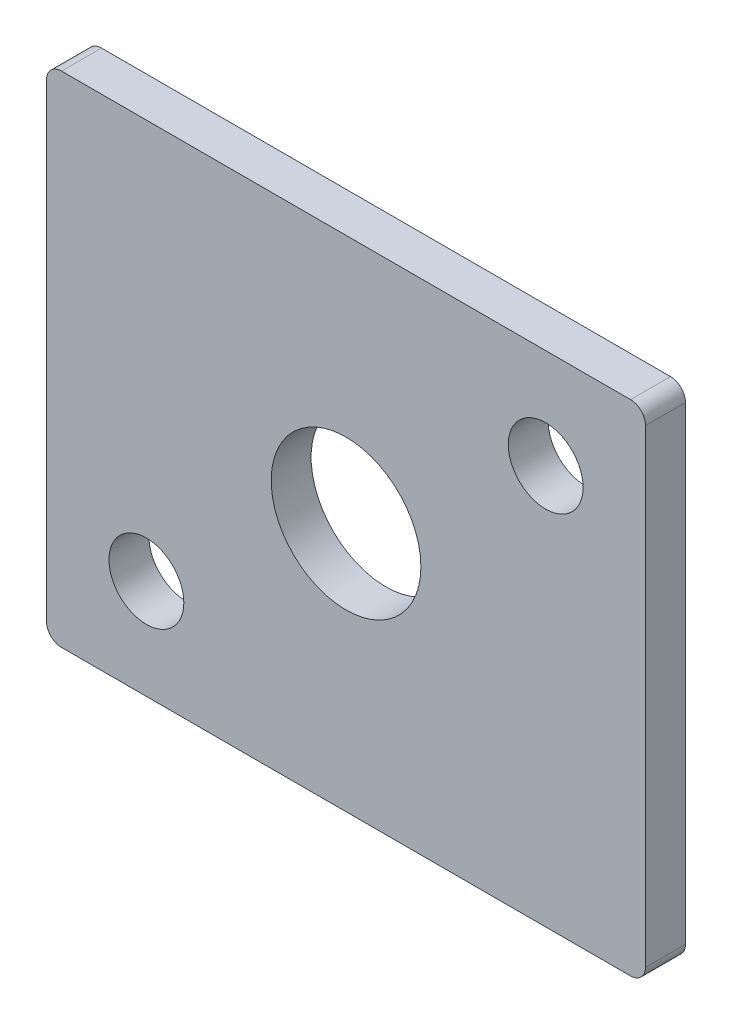
SolidWorks part; units mm, degrees
material "Messing"
ref_plane "Ebene vorne" through (0, 0, 0) normal (0, 0, 1) x (1, 0, 0)
ref_plane "Ebene oben" through (0, 0, 0) normal (0, 1, 0) x (1, 0, 0)
ref_plane "Ebene rechts" through (0, 0, 0) normal (1, 0, 0) x (0, 0, -1)
sketch "Skizze1" plane through (0, 0, 0) normal (0, 0, 1) x (1, 0, 0)
  line L1 (0, 0) -> (12, 0)
  line L2 (0, 0) -> (0, 10)
  line L3 (0, 10) -> (12, 10)
  line L4 (12, 0) -> (12, 10)
  dimension "D1" = 12
  dimension "D2" = 10
extrude "Aufsatz-Linear austragen1" add sketch "Skizze1" along normal blind 0.8
sketch "Skizze2" plane through (0, 0, 0.8) normal (0, 0, 1) x (1, 0, 0)
  line L0 (6, 10) -> (6, 5) construction
  line L1 (12, 10) -> (0, 10) construction
  line L2 (6, 5) -> (6, 0) construction
  line L3 (0, 0) -> (12, 0) construction
  line L4 (0, 10) -> (0, 0) construction
  line L5 (12, 0) -> (12, 10) construction
  circle A0 centre (2, 2) radius 0.75
  circle A1 centre (6, 5) radius 1.5
  circle A2 centre (10, 8) radius 0.75
  dimension "D1" = 3
  dimension "D2" = 1.5
  dimension "D6" = 2
  dimension "D3" = 2
  dimension "D4" = 2
  dimension "D5" = 2
extrude "Schnitt-Linear austragen1" cut sketch "Skizze2" against normal through all
fillet "Verrundung1" radius 0.3 4 edges at (0, 0, 0.4) (12, 0, 0.4) (12, 10, 0.4) (0, 10, 0.4)
